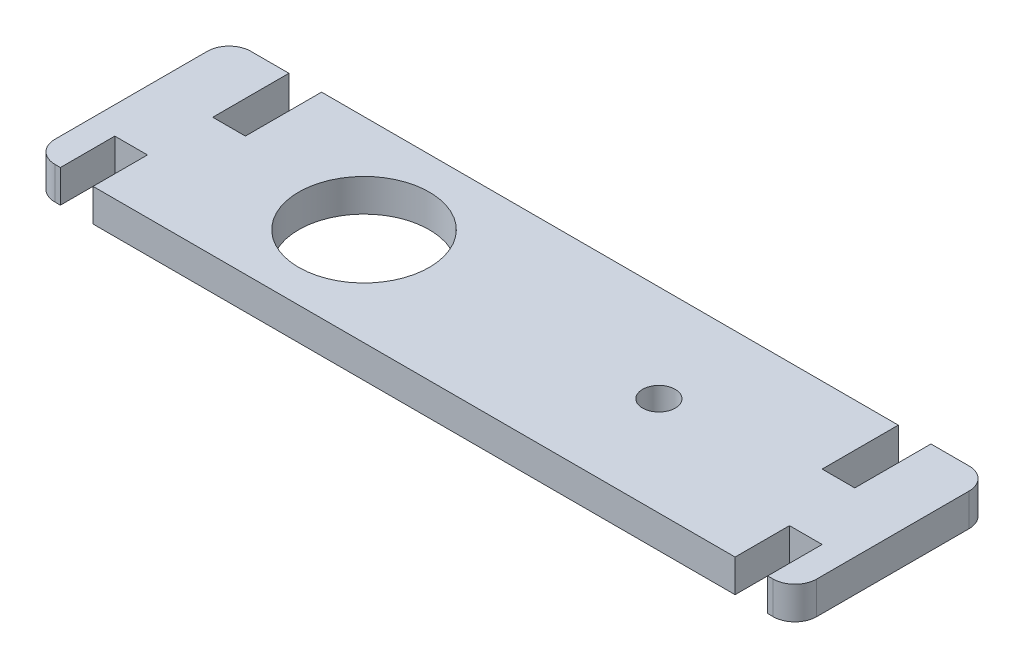
SolidWorks part; units mm, degrees
ref_plane "Front Plane" through (0, 0, 0) normal (0, 0, 1) x (1, 0, 0)
ref_plane "Top Plane" through (0, 0, 0) normal (0, 1, 0) x (1, 0, 0)
ref_plane "Right Plane" through (0, 0, 0) normal (1, 0, 0) x (0, 0, -1)
sketch "Sketch2" plane through (0, 0, 0) normal (0, 1, 0) x (1, 0, 0)
  line L0 (-3.5839, 15.8771) -> (62.4161, 15.8771)
  line L1 (64.4161, 13.8771) -> (64.4161, -0.1229)
  line L2 (62.4161, -2.1229) -> (-3.5839, -2.1229)
  line L3 (-5.5839, -0.1229) -> (-5.5839, 13.8771)
  arc A0 (62.4161, 15.8771) -> (64.4161, 13.8771) centre (62.4161, 13.8771) cw
  arc A1 (64.4161, -0.1229) -> (62.4161, -2.1229) centre (62.4161, -0.1229) cw
  arc A2 (-3.5839, -2.1229) -> (-5.5839, -0.1229) centre (-3.5839, -0.1229) cw
  arc A3 (-5.5839, 13.8771) -> (-3.5839, 15.8771) centre (-3.5839, 13.8771) cw
  dimension "D1" = 2
  dimension "D2" = 2
  dimension "D3" = 2
  dimension "D4" = 2
  dimension "D5" = 70
  dimension "D6" = 18
extrude "Boss-Extrude1" add sketch "Sketch2" along normal blind 3
sketch "Sketch6" plane through (0, 3, 0) normal (0, 1, 0) x (1, 0, 0)
  line L0 (62.4161, 15.8771) -> (-3.5839, 15.8771) construction
  line L1 (-0.0839, 15.8771) -> (2.9161, 15.8771)
  line L2 (-0.0839, 15.8771) -> (-0.0839, 8.8771)
  line L3 (-0.0839, 8.8771) -> (2.9161, 8.8771)
  line L4 (2.9161, 15.8771) -> (2.9161, 8.8771)
  line L5 (-5.5839, 13.8771) -> (-5.5839, -0.1229) construction
  line L7 (55.9161, 15.8771) -> (58.9161, 15.8771)
  line L8 (55.9161, 15.8771) -> (55.9161, 8.8771)
  line L9 (55.9161, 8.8771) -> (58.9161, 8.8771)
  line L10 (58.9161, 15.8771) -> (58.9161, 8.8771)
  line L11 (64.4161, -0.1229) -> (64.4161, 13.8771) construction
  dimension "D2" = 3
  dimension "D3" = 5.5
  dimension "D4" = 7
  dimension "D5" = 3
  dimension "D6" = 5.5
extrude "Cut-Extrude3" cut sketch "Sketch6" against normal blind 3
sketch "Sketch7" plane through (0, 3, 0) normal (0, 1, 0) x (1, 0, 0)
  line L1 (64.4161, -0.1229) -> (64.4161, 13.8771) construction
  line L2 (55.9161, 15.8771) -> (2.9161, 15.8771) construction
  circle A0 centre (42.8161, 6.9771) radius 1.5
  dimension "D1" = 3
  dimension "D2" = 8.9
  dimension "D3" = 21.6
extrude "Cut-Extrude4" cut sketch "Sketch7" against normal blind 3
sketch "Sketch8" plane through (0, 3, 0) normal (0, 1, 0) x (1, 0, 0)
  line L0 (-3.5839, -2.1229) -> (62.4161, -2.1229) construction
  line L1 (58.9161, -2.1229) -> (61.9161, -2.1229)
  line L2 (58.9161, -2.1229) -> (58.9161, 2.8771)
  line L3 (58.9161, 2.8771) -> (61.9161, 2.8771)
  line L4 (61.9161, -2.1229) -> (61.9161, 2.8771)
  line L5 (58.9161, 8.8771) -> (58.9161, 15.8771) construction
  line L6 (-0.0839, 15.8771) -> (-0.0839, 8.8771) construction
  line L7 (-0.0839, -2.1229) -> (-3.0839, -2.1229)
  line L8 (-0.0839, -2.1229) -> (-0.0839, 2.8771)
  line L9 (-0.0839, 2.8771) -> (-3.0839, 2.8771)
  line L10 (-3.0839, -2.1229) -> (-3.0839, 2.8771)
  dimension "D1" = 3
  dimension "D2" = 5
  dimension "D3" = 3
  dimension "D4" = 5
extrude "Cut-Extrude5" cut sketch "Sketch8" against normal blind 3
sketch "Sketch9" plane through (0, 3, 0) normal (0, 1, 0) x (1, 0, 0)
  line L0 (55.9161, 15.8771) -> (2.9161, 15.8771) construction
  line L1 (-5.5839, 13.8771) -> (-5.5839, -0.1229) construction
  circle A0 centre (15.8161, 6.8771) radius 6
  dimension "D1" = 12
  dimension "D2" = 9
  dimension "D3" = 21.4
extrude "Cut-Extrude6" cut sketch "Sketch9" against normal blind 3
